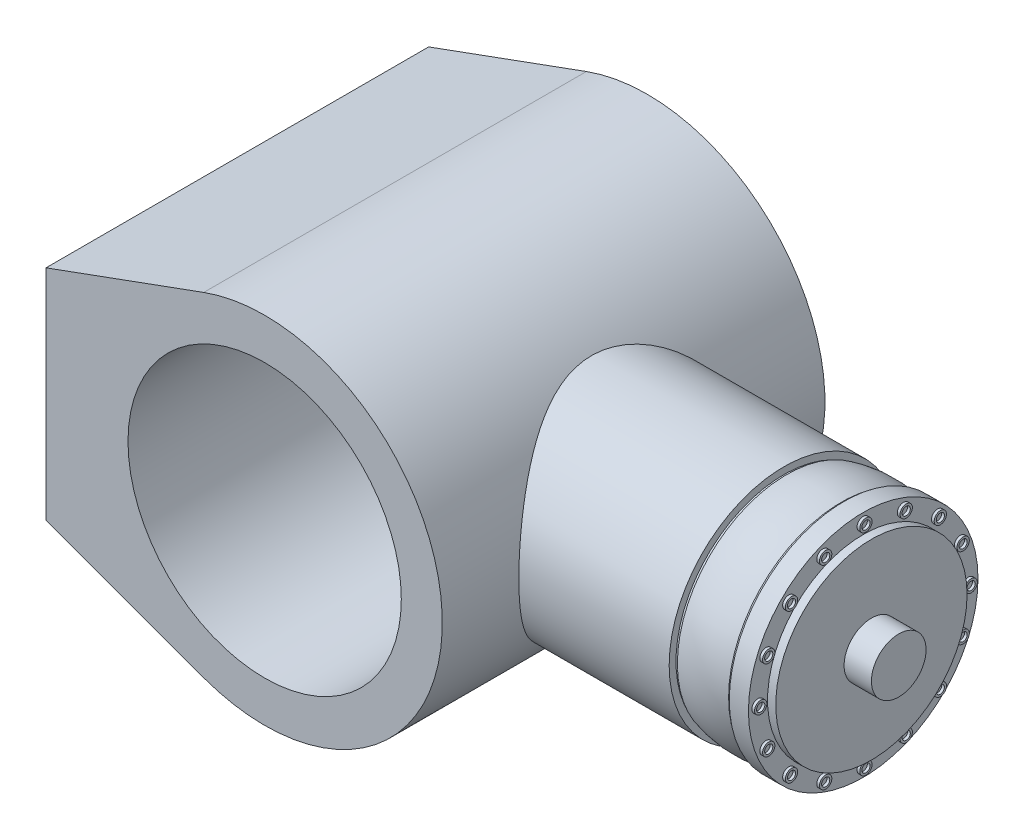
SolidWorks part; units mm, degrees
ref_plane "Front Plane" through (0, 0, 0) normal (0, 0, 1) x (1, 0, 0)
ref_plane "Top Plane" through (0, 0, 0) normal (0, 1, 0) x (1, 0, 0)
ref_plane "Right Plane" through (0, 0, 0) normal (1, 0, 0) x (0, 0, -1)
sketch "Sketch1" plane through (0, 0, 0) normal (0, 0, 1) x (1, 0, 0)
  line L0 (-80, -40) -> (-80, 40)
  line L1 (-80, 40) -> (-22.2817, 61.0617)
  line L2 (-80, -40) -> (-22.2817, -61.0617)
  arc A0 (-22.2817, -61.0617) -> (-22.2817, 61.0617) centre (0, 0) ccw
  circle A1 centre (0, 0) radius 50
  point P7 (-80, 0)
  dimension "D1" = 130
  dimension "D2" = 100
  dimension "D3" = 80
  dimension "D4" = 80
extrude "Boss-Extrude1" add sketch "Sketch1" along normal mid plane 140
ref_plane "Plane1" through (120, 0, 0) normal (1, 0, 0) x (0, 0, -1)
sketch "Sketch2" plane through (120, 0, 0) normal (1, 0, 0) x (0, 0, -1)
  circle A0 centre (0, 0) radius 42
  dimension "D1" = 84
extrude "Boss-Extrude2" add sketch "Sketch2" against normal up to next
sketch "Sketch3" plane through (120, 0, 0) normal (1, 0, 0) x (0, 0, -1)
  circle A0 centre (0, 0) radius 39.5
  dimension "D1" = 79
extrude "Boss-Extrude3" add sketch "Sketch3" along normal blind 1
sketch "Sketch5" plane through (0, 0, 0) normal (0, 0, 1) x (1, 0, 0)
  line L0 (121, 0) -> (121, 40)
  line L1 (121, -39.5) -> (121, 39.5) construction
  line L2 (121, 0) -> (141, 0)
  line L3 (141, 0) -> (141, 40)
  arc A1 (121, 40) -> (141, 40) centre (131, 4.377) cw
  dimension "D3" = 37
  dimension "D1" = 40
  dimension "D2" = 20
revolve "Revolve1" add sketch "Sketch5" angle 360 about L2
sketch "Sketch6" plane through (141, 0, 0) normal (1, 0, 0) x (0, 0, -1)
  circle A0 centre (0, 0) radius 41.25
  dimension "D1" = 82.5
extrude "Boss-Extrude4" add sketch "Sketch6" along normal blind 1
sketch "Sketch7" plane through (142, 0, 0) normal (1, 0, 0) x (0, 0, -1)
  circle A0 centre (0, 0) radius 42
  dimension "D1" = 84
extrude "Boss-Extrude5" add sketch "Sketch7" along normal blind 7
sketch "Sketch8" plane through (149, 0, 0) normal (1, 0, 0) x (0, 0, -1)
  circle A0 centre (0, 0) radius 35
  dimension "D1" = 70
extrude "Boss-Extrude6" add sketch "Sketch8" along normal blind 3
sketch "Sketch9" plane through (149, 0, 0) normal (1, 0, 0) x (0, 0, -1)
  circle A3 centre (38.5, 0) radius 2.25
  circle A4 centre (38.5, 0) radius 1.5
  dimension "D1" = 4.5
  dimension "D2" = 3
extrude "Boss-Extrude8" add sketch "Sketch9" along normal blind 1 contours A3 A4
pattern_circular "CirPattern1" count 16 over 360 about axis through (0, 0, 0) along (1, 0, 0) of "Boss-Extrude5", "Boss-Extrude8"
sketch "Sketch10" plane through (152, 0, 0) normal (1, 0, 0) x (0, 0, -1)
  circle A0 centre (0, 0) radius 10
  dimension "D1" = 20
extrude "Boss-Extrude9" add sketch "Sketch10" along normal blind 10
